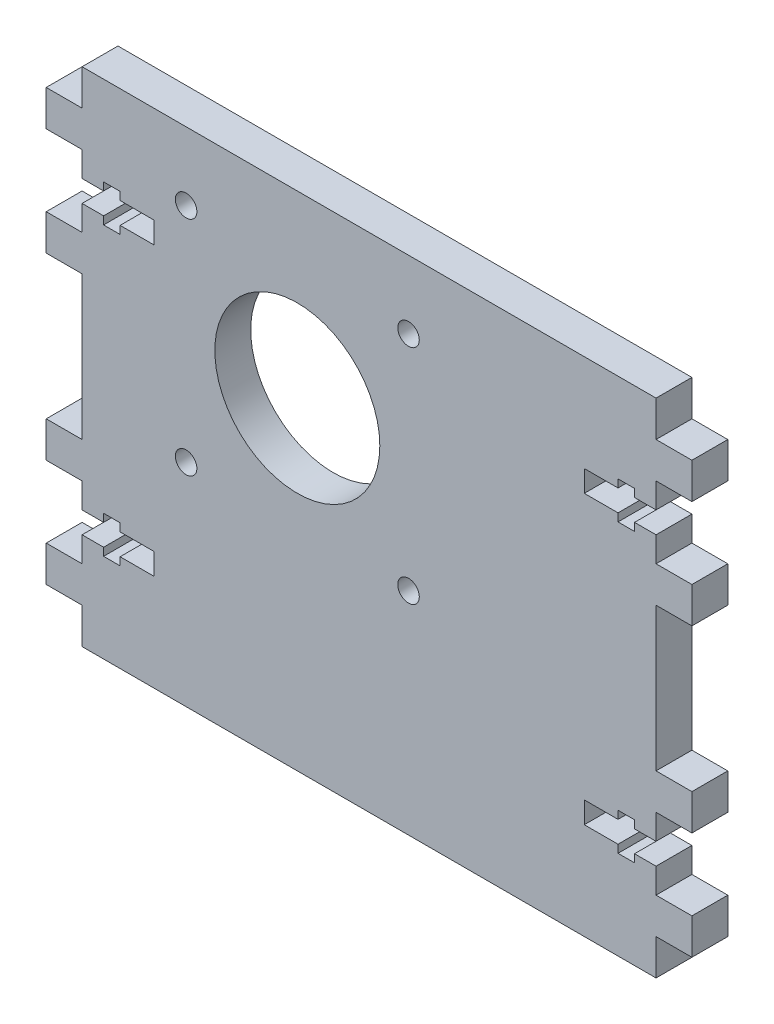
SolidWorks part; units mm, degrees
ref_plane "Front Plane" through (0, 0, 0) normal (0, 0, 1) x (1, 0, 0)
ref_plane "Top Plane" through (0, 0, 0) normal (0, 1, 0) x (1, 0, 0)
ref_plane "Right Plane" through (0, 0, 0) normal (1, 0, 0) x (0, 0, -1)
sketch "Sketch1" plane through (0, 0, 0) normal (0, 0, 1) x (1, 0, 0)
  line L0 (0, 0) -> (0, 70) construction
  line L1 (0, 70) -> (-80, 70)
  line L4 (-40, 38.7693) -> (-40, -40.9046) construction
  line L5 (0, 35) -> (-37.6147, 35) construction
  line L6 (0, 55) -> (-11.2208, 55) construction
  line L7 (0, 53.5) -> (0, 50)
  line L8 (5, 50) -> (5, 45)
  line L9 (5, 45) -> (0, 45)
  line L10 (5, 50) -> (0, 50)
  line L11 (0, 56.5) -> (0, 60)
  line L12 (0, 60) -> (5, 60)
  line L13 (5, 60) -> (5, 65)
  line L14 (5, 65) -> (0, 65)
  line L15 (0, 53.5) -> (0, 56.5) construction
  line L16 (0, 56.5) -> (-3, 56.5)
  line L17 (-5.3, 56.5) -> (-5.3, 57.6)
  line L18 (-3, 52.4) -> (-5.3, 52.4)
  line L19 (-3, 57.6) -> (-3, 56.5)
  line L20 (-5.3, 56.5) -> (-10, 56.5)
  line L21 (-10, 56.5) -> (-10, 53.5)
  line L22 (-10, 53.5) -> (-5.3, 53.5)
  line L23 (-3, 53.5) -> (-3, 52.4)
  line L24 (-5.3, 57.6) -> (-3, 57.6)
  line L25 (-5.3, 52.4) -> (-5.3, 53.5)
  line L26 (-3, 53.5) -> (0, 53.5)
  line L27 (-10, 55) -> (0, 55) construction
  line L66 (-85, 65) -> (-80, 65)
  line L67 (-85, 60) -> (-85, 65)
  line L68 (-80, 60) -> (-85, 60)
  line L69 (-80, 56.5) -> (-80, 60)
  line L70 (-80, 56.5) -> (-77, 56.5)
  line L71 (-77, 57.6) -> (-77, 56.5)
  line L72 (-74.7, 57.6) -> (-77, 57.6)
  line L73 (-74.7, 56.5) -> (-74.7, 57.6)
  line L74 (-74.7, 56.5) -> (-70, 56.5)
  line L75 (-70, 56.5) -> (-70, 53.5)
  line L76 (-70, 53.5) -> (-74.7, 53.5)
  line L77 (-74.7, 52.4) -> (-74.7, 53.5)
  line L78 (-77, 52.4) -> (-74.7, 52.4)
  line L79 (-77, 53.5) -> (-77, 52.4)
  line L80 (-77, 53.5) -> (-80, 53.5)
  line L81 (-80, 53.5) -> (-80, 50)
  line L82 (-85, 50) -> (-80, 50)
  line L83 (-85, 50) -> (-85, 45)
  line L84 (-85, 45) -> (-80, 45)
  line L85 (-80, 70) -> (-80, 65)
  line L90 (0, 65) -> (0, 70)
  line L91 (-85, 25) -> (-80, 25)
  line L92 (-85, 20) -> (-85, 25)
  line L93 (-85, 20) -> (-80, 20)
  line L94 (-80, 16.5) -> (-80, 20)
  line L95 (-77, 16.5) -> (-80, 16.5)
  line L96 (-77, 16.5) -> (-77, 17.6)
  line L97 (-77, 17.6) -> (-74.7, 17.6)
  line L98 (-74.7, 17.6) -> (-74.7, 16.5)
  line L99 (-70, 16.5) -> (-74.7, 16.5)
  line L100 (-70, 13.5) -> (-70, 16.5)
  line L101 (-74.7, 13.5) -> (-70, 13.5)
  line L102 (-74.7, 13.5) -> (-74.7, 12.4)
  line L103 (-74.7, 12.4) -> (-77, 12.4)
  line L104 (-77, 12.4) -> (-77, 13.5)
  line L105 (-80, 13.5) -> (-77, 13.5)
  line L106 (-80, 13.5) -> (-80, 10)
  line L107 (-80, 10) -> (-85, 10)
  line L108 (-85, 10) -> (-85, 5)
  line L109 (-85, 5) -> (-80, 5)
  line L110 (-80, 0) -> (-80, 5)
  line L111 (0, 0) -> (-80, 0)
  line L112 (0, 5) -> (0, 0)
  line L113 (5, 5) -> (0, 5)
  line L114 (5, 10) -> (5, 5)
  line L115 (0, 10) -> (5, 10)
  line L116 (0, 13.5) -> (0, 10)
  line L117 (0, 13.5) -> (-3, 13.5)
  line L118 (-3, 12.4) -> (-3, 13.5)
  line L119 (-5.3, 12.4) -> (-3, 12.4)
  line L120 (-5.3, 13.5) -> (-5.3, 12.4)
  line L121 (-5.3, 13.5) -> (-10, 13.5)
  line L122 (-10, 13.5) -> (-10, 16.5)
  line L123 (-10, 16.5) -> (-5.3, 16.5)
  line L124 (-5.3, 17.6) -> (-5.3, 16.5)
  line L125 (-3, 17.6) -> (-5.3, 17.6)
  line L126 (-3, 16.5) -> (-3, 17.6)
  line L127 (-3, 16.5) -> (0, 16.5)
  line L128 (0, 16.5) -> (0, 20)
  line L129 (5, 20) -> (0, 20)
  line L130 (5, 20) -> (5, 25)
  line L131 (5, 25) -> (0, 25)
  line L132 (-80, 45) -> (-80, 25)
  line L133 (0, 45) -> (0, 25)
  circle B0 centre (-65.5, 60.5) radius 1.5
  circle B1 centre (-34.5, 60.5) radius 1.5
  circle B2 centre (-34.5, 29.5) radius 1.5
  circle B3 centre (-65.5, 29.5) radius 1.5
  circle B4 centre (-50, 45) radius 11.5
  line B5 (-34.5, 60.5) -> (-34.5, 29.5) construction
  line B6 (-65.5, 29.5) -> (-65.5, 60.5) construction
  line B7 (-34.5, 29.5) -> (-65.5, 29.5) construction
  dimension "D2" = 40
  dimension "D3" = 80
  dimension "D4" = 10
  dimension "D5" = 5
  dimension "D6" = 5
  dimension "D7" = 5.2
  dimension "D8" = 3
  dimension "D9" = 2.3
  dimension "D10" = 3
  dimension "D11" = 10
  dimension "D12" = 70
  dimension "D13" = 15
  dimension "D14" = 50
  dimension "D15" = 10
sketch_block_instance "Fixation Nema 17-1"
sketch_block "Fixation Nema 17" parameters "D3"=3, "D4"=23, "D1"=31.844, "D2"=31.844
extrude "Boss-Extrude1" add sketch "Sketch1" along normal blind 5
